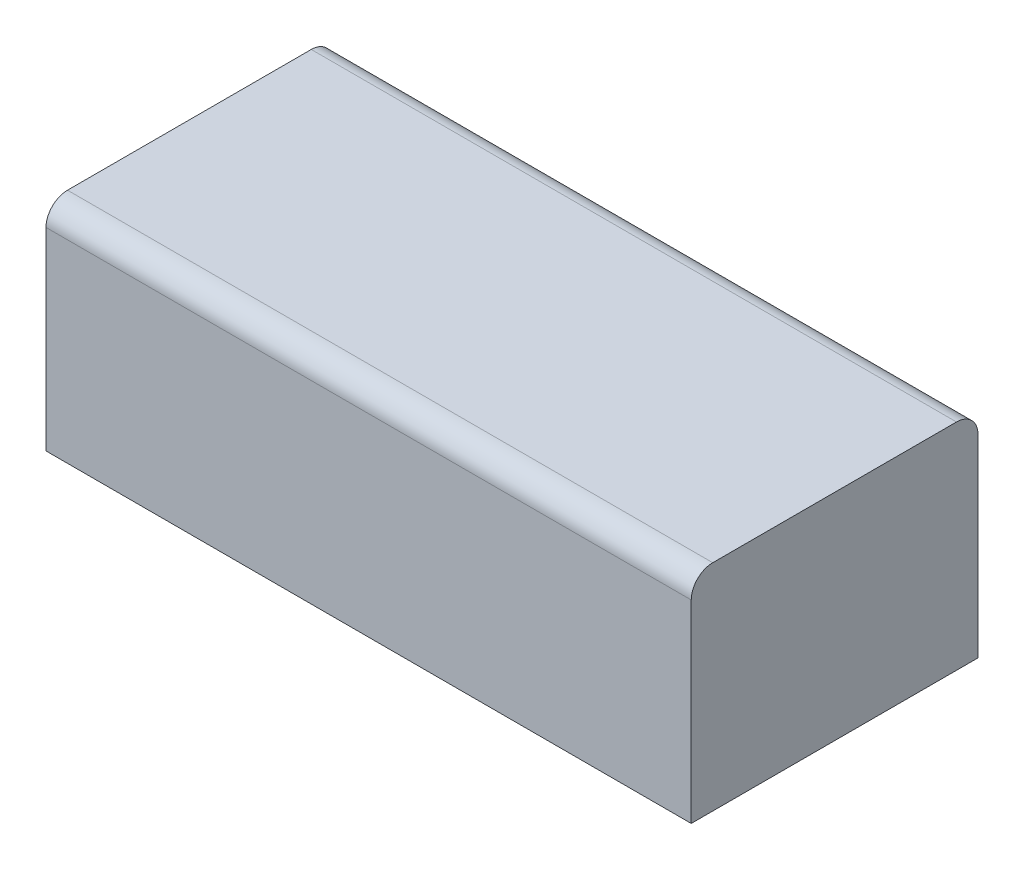
SolidWorks part; units mm, degrees
ref_plane "Front Plane" through (0, 0, 0) normal (0, 0, 1) x (1, 0, 0)
ref_plane "Top Plane" through (0, 0, 0) normal (0, 1, 0) x (1, 0, 0)
ref_plane "Right Plane" through (0, 0, 0) normal (1, 0, 0) x (0, 0, -1)
sketch "Sketch1" plane through (0, 0, 0) normal (0, 1, 0) x (1, 0, 0)
  line L1 (0, 0) -> (90, 0)
  line L2 (0, 0) -> (0, 40)
  line L3 (0, 40) -> (90, 40)
  line L4 (90, 0) -> (90, 40)
  dimension "D1" = 90
  dimension "D2" = 40
extrude "Boss-Extrude1" add sketch "Sketch1" along normal blind 30
fillet "Fillet1" radius 3 1 edges at (45, 30, 0)
fillet "Fillet2" radius 3 1 edges at (45, 30, -40)
